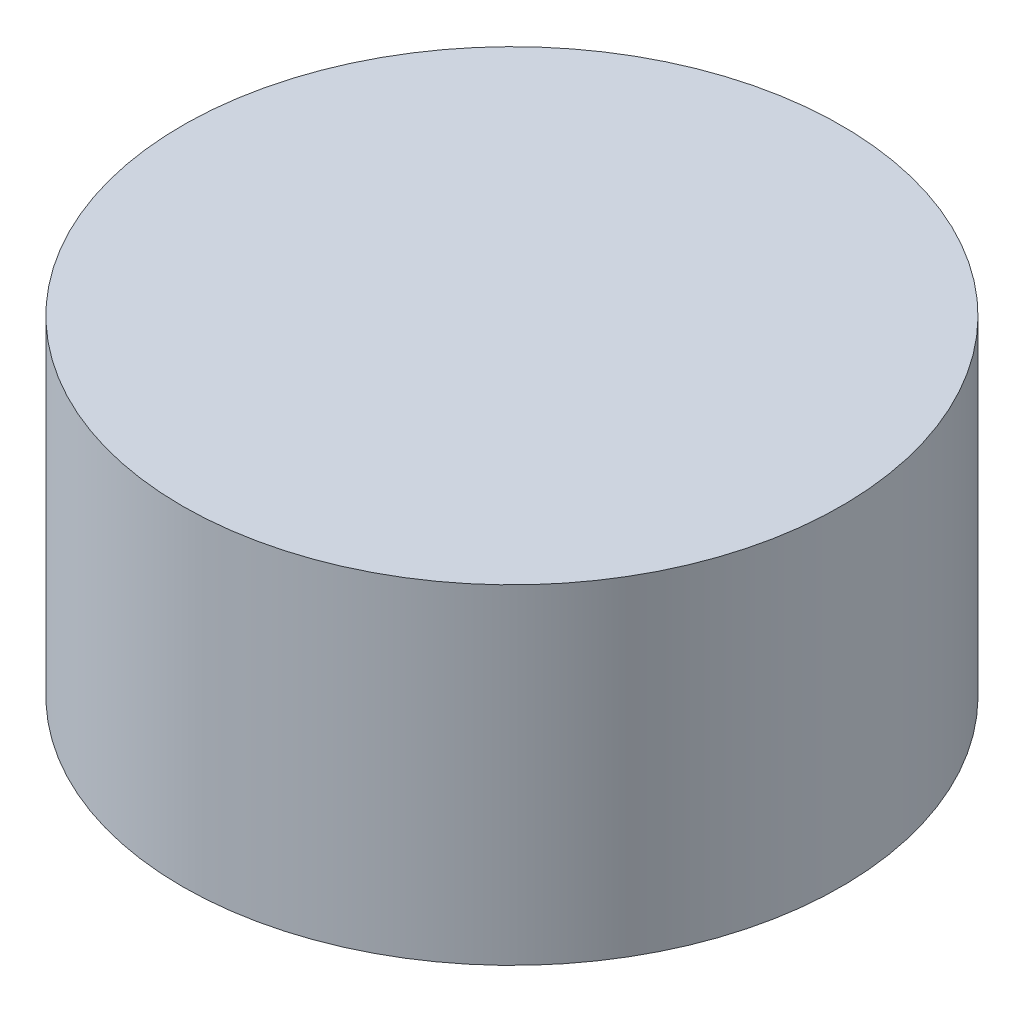
SolidWorks part; units mm, degrees
material "AISI 304"
ref_plane "Front Plane" through (0, 0, 0) normal (0, 0, 1) x (1, 0, 0)
ref_plane "Top Plane" through (0, 0, 0) normal (0, 1, 0) x (1, 0, 0)
ref_plane "Right Plane" through (0, 0, 0) normal (1, 0, 0) x (0, 0, -1)
sketch "Sketch1" plane through (0, 0, 0) normal (0, 1, 0) x (1, 0, 0)
  circle A0 centre (0, 0) radius 9
  dimension "D1" = 18
extrude "Boss-Extrude1" add sketch "Sketch1" along normal blind 9
sketch "Sketch2" plane through (0, 9, 0) normal (0, 1, 0) x (1, 0, 0)
  circle A0 centre (0, 0) radius 6.35
  dimension "D1" = 12.7
extrude "Cut-Extrude1" [suppressed] cut sketch "Sketch2" against normal through all
equation "\"D1@Sketch2\"=\"BaseInnerDiam\""
equation "\"D1@Sketch1\"=\"WeightOuterDiam\""
equation "\"PawnHeight\"= 1mm"
equation "\"MagDiam\"= 12mm"
equation "\"MagThickness\"= 3mm"
equation "\"KnightHeight\"= 2.5mm"
equation "\"RookHeight\"= 4mm"
equation "\"BishopHeight\"= 5.5mm"
equation "\"QueenHeight\"= 6.5mm"
equation "\"KingHeight\"= 8mm"
equation "\"WeightOuterDiam\"= 18mm"
equation "\"WeightInnerDiam\"= \"MagDiam\" + 0.3mm"
equation "\"WeightHeight\"= 9mm"
equation "\"BaseOuterDiam\" = 20mm"
equation "\"BaseInnerDiam\" = 12.7mm"
equation "\"FeltThickness\" = 1mm"
